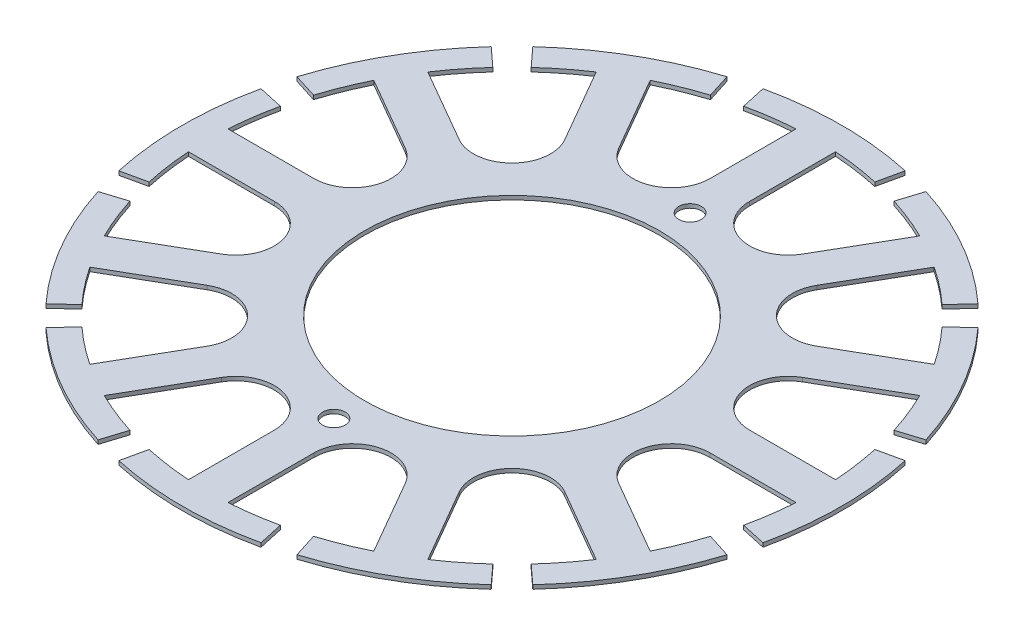
SolidWorks part; units mm, degrees
ref_plane "Front Plane" through (0, 0, 0) normal (0, 0, 1) x (1, 0, 0)
ref_plane "Top Plane" through (0, 0, 0) normal (0, 1, 0) x (1, 0, 0)
ref_plane "Right Plane" through (0, 0, 0) normal (1, 0, 0) x (0, 0, -1)
sketch "Sketch2" plane through (0, 0, 0) normal (0, 0, 1) x (1, 0, 0)
  line L0 (0, 0) -> (0, 17.2966) construction
  line L1 (13.05, 0) -> (29.2, 0)
  line L2 (29.2, 0) -> (29.2, 0.35)
  line L3 (29.2, 0.35) -> (13.05, 0.35)
  line L4 (13.05, 0.35) -> (13.05, 0)
  dimension "D1" = 13.05
  dimension "D2" = 29.2
  dimension "D3" = 0.35
revolve "Revolve2" add sketch "Sketch2" angle 360 about L0
sketch "Sketch3" plane through (0, 0.35, 0) normal (0, 1, 0) x (1, 0, 0)
  line L0 (0, 0) -> (0, 29.2) construction
  line L1 (0, 0) -> (-4.0639, 28.9158) construction
  line L2 (0, 0) -> (-7.5575, 28.205) construction
  line L3 (0, 0) -> (-10.9385, 27.0738) construction
  line L4 (-1.75, 26.8931) -> (-1.75, 19.2877)
  line L5 (-11.931, 24.1651) -> (-8.1283, 17.5787)
  line L6 (-6.2942, 28.5136) -> (-5.8092, 26.3164)
  line L7 (-8.8058, 27.8406) -> (-8.1273, 25.6953)
  circle A0 centre (0, 0) radius 29.2 construction
  circle A1 centre (0, 0) radius 16.55
  arc A2 (-8.1283, 17.5787) -> (-1.75, 19.2877) centre (-5.1681, 19.2877) ccw
  circle A3 centre (0, 0) radius 26.95 construction
  arc A4 (-6.2942, 28.5136) -> (-1.75, 29.1475) centre (0, 0) cw
  arc A6 (-5.8092, 26.3164) -> (-1.75, 26.8931) centre (0, 0) cw
  arc A8 (-8.1273, 25.6953) -> (-11.931, 24.1651) centre (0, 0) ccw
  arc A9 (-8.8058, 27.8406) -> (-13.0582, 26.1175) centre (0, 0) ccw
  point P20 (-6.0517, 27.415)
  point P26 (-1.75, 23.0904)
  dimension "D1" = 33.1
  dimension "D5" = 53.9
  dimension "D6" = 2.5
  dimension "D4" = 3.5
  dimension "D2" = 8
  dimension "D3" = 15
extrude "Cut-Extrude5" cut sketch "Sketch3" against normal through all both and the other way through all contours L7 A8 L5 A2 L4 A6 L6 A0
pattern_circular "CirPattern1" count 12 over 360 about axis through (0, 0, 0) along (0, 1, 0) of "Cut-Extrude5"
sketch "Sketch5" plane through (0, 0.35, 0) normal (0, 1, 0) x (1, 0, 0)
  line L0 (0, 13.05) -> (0, 18.4819) construction
  circle A0 centre (0, 0) radius 13.05 construction
  circle A1 centre (0, 15.7659) radius 1
  circle A2 centre (0, -15.7659) radius 1
  point P13 (0, 0)
  dimension "D1" = 2
  dimension "D2" = 15.7659
  dimension "D3" = 15.7659
  dimension "D4" = 2
extrude "Cut-Extrude6" cut sketch "Sketch5" against normal through all both and the other way through all contours A1 | A2
equation "\"stator inner rad\"= 13.05"
equation "\"stator outer rad\"= 29.2"
equation "\"D1@Sketch2\"=\"stator inner rad\""
equation "\"D2@Sketch2\"=\"stator outer rad\""
equation "\"D1@Sketch3\"=((\"stator inner rad\")*2)+7"
equation "\"D5@Sketch3\"=((\"stator outer rad\")*2)-4.5"
